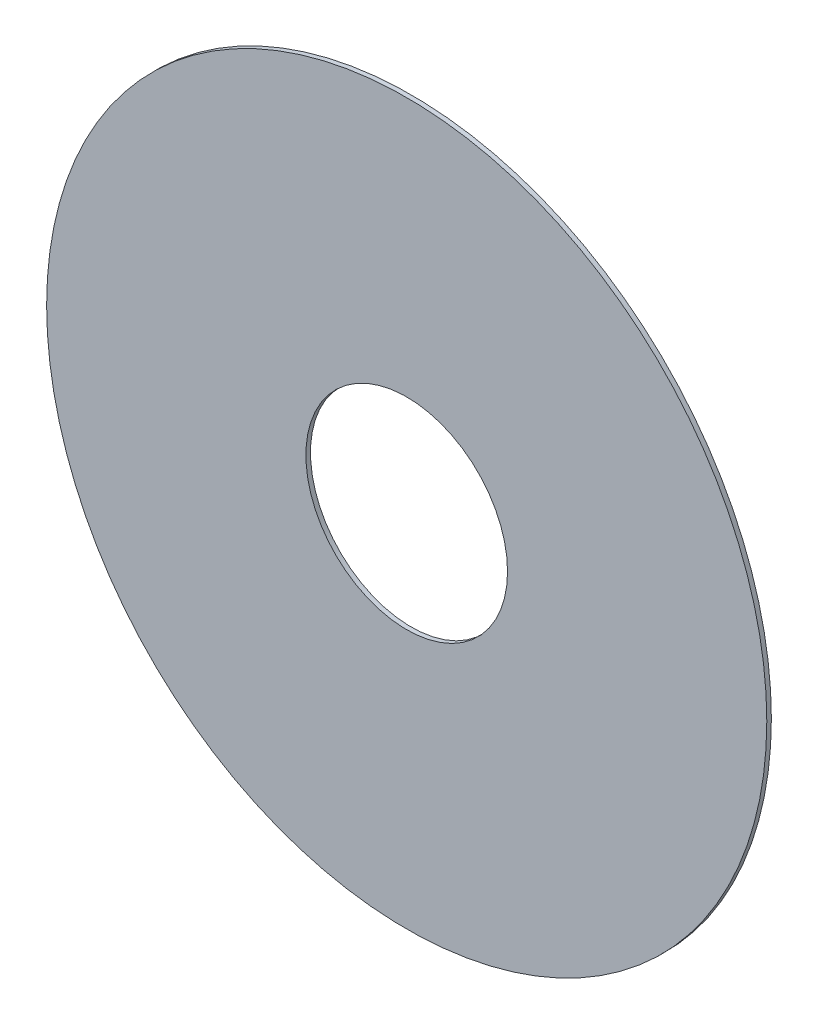
SolidWorks part; units mm, degrees
ref_plane "Front Plane" through (0, 0, 0) normal (0, 0, 1) x (1, 0, 0)
ref_plane "Top Plane" through (0, 0, 0) normal (0, 1, 0) x (1, 0, 0)
ref_plane "Right Plane" through (0, 0, 0) normal (1, 0, 0) x (0, 0, -1)
sketch "Sketch1" plane through (0, 0, 0) normal (0, 0, 1) x (1, 0, 0)
  circle A0 centre (0, 0) radius 250
  dimension "D1" = 500
extrude "Boss-Extrude2" add sketch "Sketch1" along normal blind 3.175
sketch "Sketch2" plane through (0, 0, 3.175) normal (0, 0, 1) x (1, 0, 0)
  circle A0 centre (0, 0) radius 70
  dimension "D1" = 140
extrude "Cut-Extrude1" cut sketch "Sketch2" against normal blind 3.175
